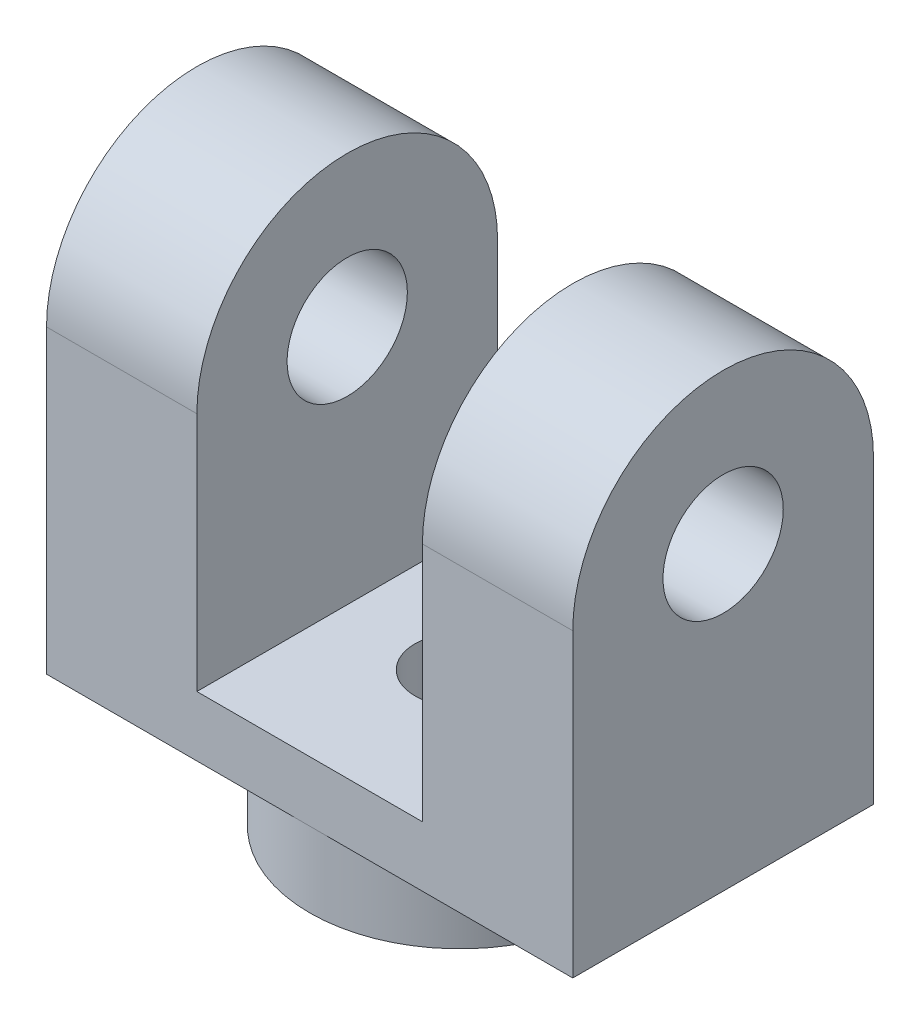
SolidWorks part; units mm, degrees
ref_plane "Front" through (0, 0, 0) normal (0, 0, 1) x (1, 0, 0)
ref_plane "Top" through (0, 0, 0) normal (0, 1, 0) x (1, 0, 0)
ref_plane "Right" through (0, 0, 0) normal (1, 0, 0) x (0, 0, -1)
sketch "Sketch1" plane through (0, 0, 0) normal (0, 1, 0) x (1, 0, 0)
  circle A0 centre (0, 0) radius 37.5
  circle A1 centre (0, 0) radius 50
  dimension "D1" = 75
  dimension "D2" = 100
extrude "Boss-Extrude1" add sketch "Sketch1" against normal blind 25 contours A1 A0
sketch "Sketch2" plane through (0, 0, 0) normal (1, 0, 0) x (0, 0, -1)
  line L0 (-50, 0) -> (50, 0)
  line L1 (50, 0) -> (50, 100)
  line L2 (-50, 100) -> (-50, 0)
  line L3 (50, 0) -> (-50, 0) construction
  line L4 (-50, 0) -> (-50, -25) construction
  arc A0 (50, 100) -> (-50, 100) centre (0, 100) ccw
  dimension "D1" = 100
  dimension "D2" = 100
extrude "Boss-Extrude2" add sketch "Sketch2" along normal mid plane 175 contours A0 L2 L0 L1
sketch "Sketch3" plane through (0, 0, 50) normal (0, 0, 1) x (1, 0, 0)
  line L0 (-87.5, 150) -> (87.5, 150) construction
  line L2 (-37.5, 150) -> (37.5, 150)
  line L3 (-37.5, 150) -> (-37.5, 20)
  line L4 (-37.5, 20) -> (37.5, 20)
  line L5 (37.5, 150) -> (37.5, 20)
  point P8 (0, 150)
  dimension "D1" = 75
  dimension "D2" = 130
extrude "Cut-Extrude1" cut sketch "Sketch3" against normal through all both and the other way through all
sketch "Sketch4" plane through (0, 20, 0) normal (0, 1, 0) x (1, 0, 0)
  circle A0 centre (0, 0) radius 15
  dimension "D1" = 30
extrude "Cut-Extrude2" cut sketch "Sketch4" against normal through all
sketch "Sketch5" plane through (87.5, 0, 0) normal (1, 0, 0) x (0, 0, -1)
  circle A0 centre (0, 100) radius 20
  dimension "D1" = 40
extrude "Cut-Extrude3" cut sketch "Sketch5" against normal through all
